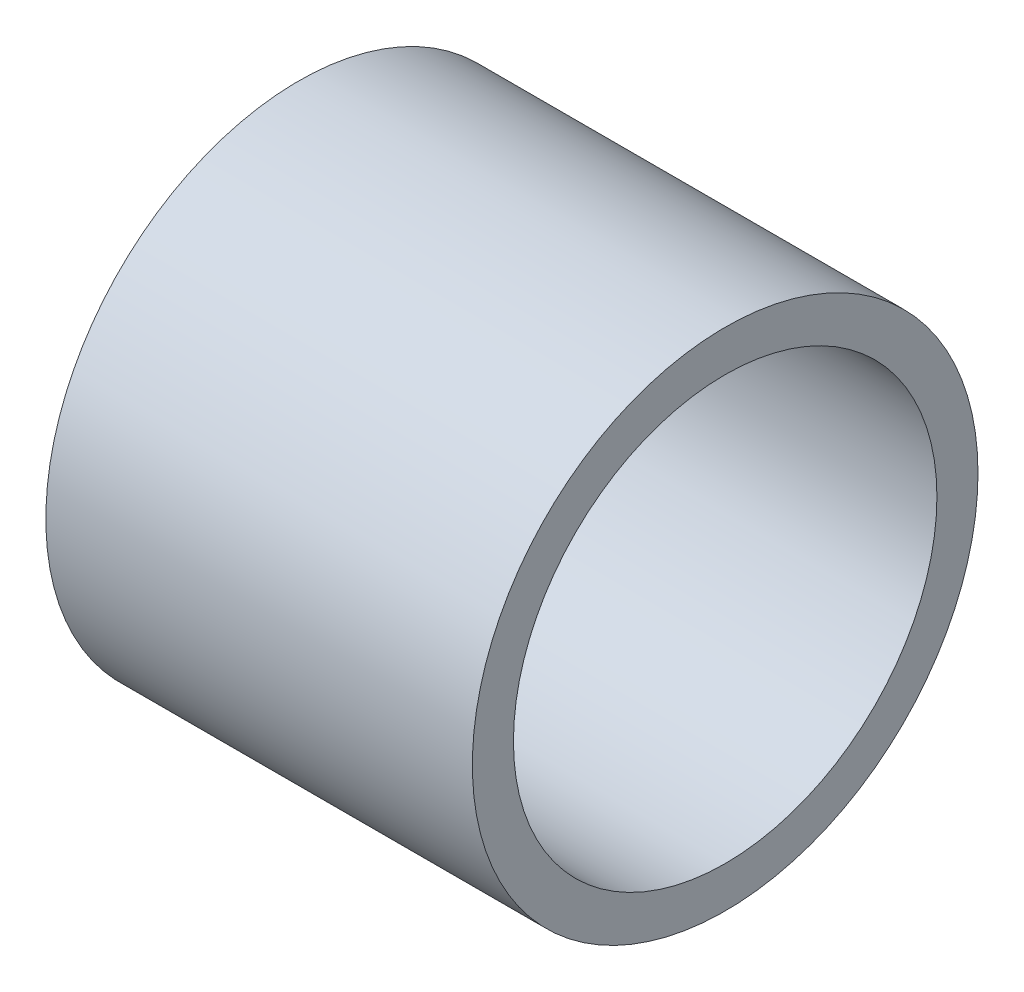
SolidWorks part; units mm, degrees
ref_plane "front" through (0, 0, 0) normal (0, 0, 1) x (1, 0, 0)
ref_plane "top" through (0, 0, 0) normal (0, 1, 0) x (1, 0, 0)
ref_plane "right" through (0, 0, 0) normal (1, 0, 0) x (0, 0, -1)
sketch "Sketch1" plane through (0, 0, 0) normal (1, 0, 0) x (0, 0, -1)
  circle A0 centre (0, 0) radius 19.0754
  circle A1 centre (0, 0) radius 15.9766
  dimension "D1" = 38.1508
  dimension "D2" = 31.9532
extrude "Extrude1" add sketch "Sketch1" along normal blind 32.1818
